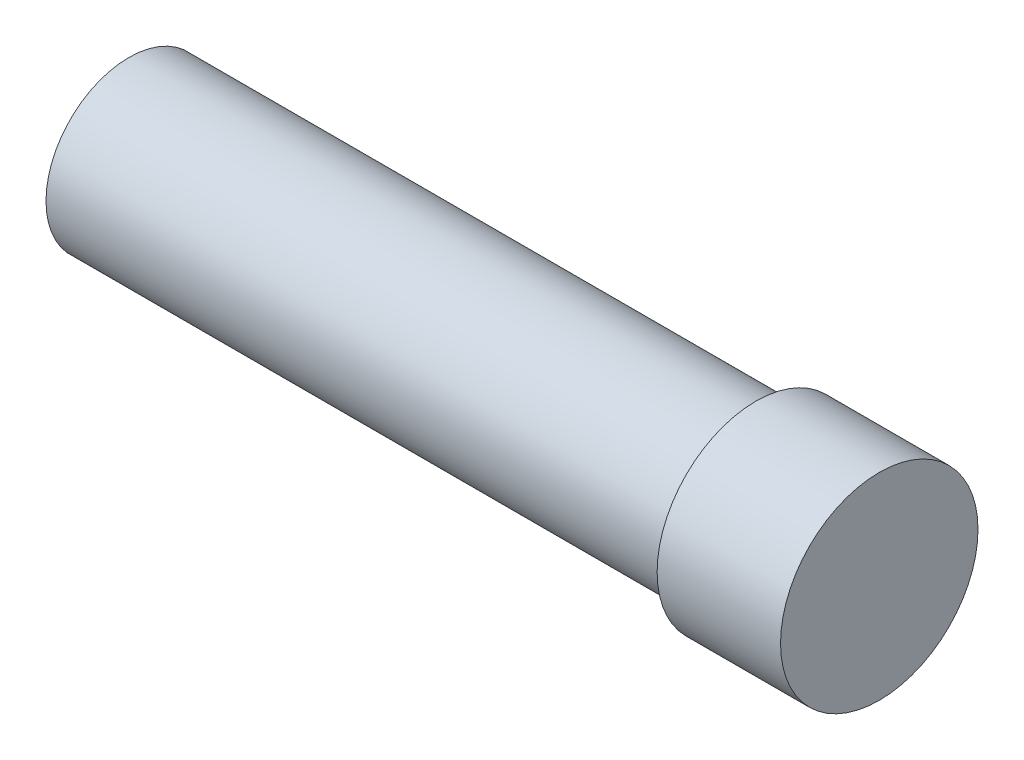
SolidWorks part; units mm, degrees
material "ABS"
ref_plane "Front Plane" through (0, 0, 0) normal (0, 0, 1) x (1, 0, 0)
ref_plane "Top Plane" through (0, 0, 0) normal (0, 1, 0) x (1, 0, 0)
ref_plane "Right Plane" through (0, 0, 0) normal (1, 0, 0) x (0, 0, -1)
sketch "Sketch1" plane through (0, 0, 0) normal (1, 0, 0) x (0, 0, -1)
  circle A0 centre (0, 0) radius 5.08
  dimension "D1" = 10.16
extrude "Boss-Extrude1" add sketch "Sketch1" along normal blind 6.35
sketch "Sketch2" plane through (0, 0, 0) normal (-1, 0, 0) x (0, 0, 1)
  circle A0 centre (0, 0) radius 4.2672
  dimension "D1" = 8.5344
extrude "Boss-Extrude2" add sketch "Sketch2" along normal blind 32.258
hole_wizard "#21 (0.159) Diameter Hole1" positions "Sketch4" profile "Sketch3" hole size "#21" standard "ANSI Inch"
sketch "Sketch4" plane through (-32.258, 0, 0) normal (-1, 0, 0) x (0, 0, 1)
  point P0 (0, 0)
sketch "Sketch3" plane through (-32.258, 0, 0) normal (0, 1, 0) x (0, 0, 1)
  line L0 (0, 0) -> (0, 12.7)
  line L1 (0, 12.7) -> (2, 12.7)
  line L2 (2, 12.7) -> (2, 0)
  line L5 (2, 0) -> (0, 0)
  line L10 (0, 12.7) -> (-2, 12.7) construction
  line L11 (0, -6.35) -> (0, 107.95) construction
  dimension "Hole Dia." = 4
  dimension "Hole Depth" = 12.7
  dimension "Drill Angle" = 180
